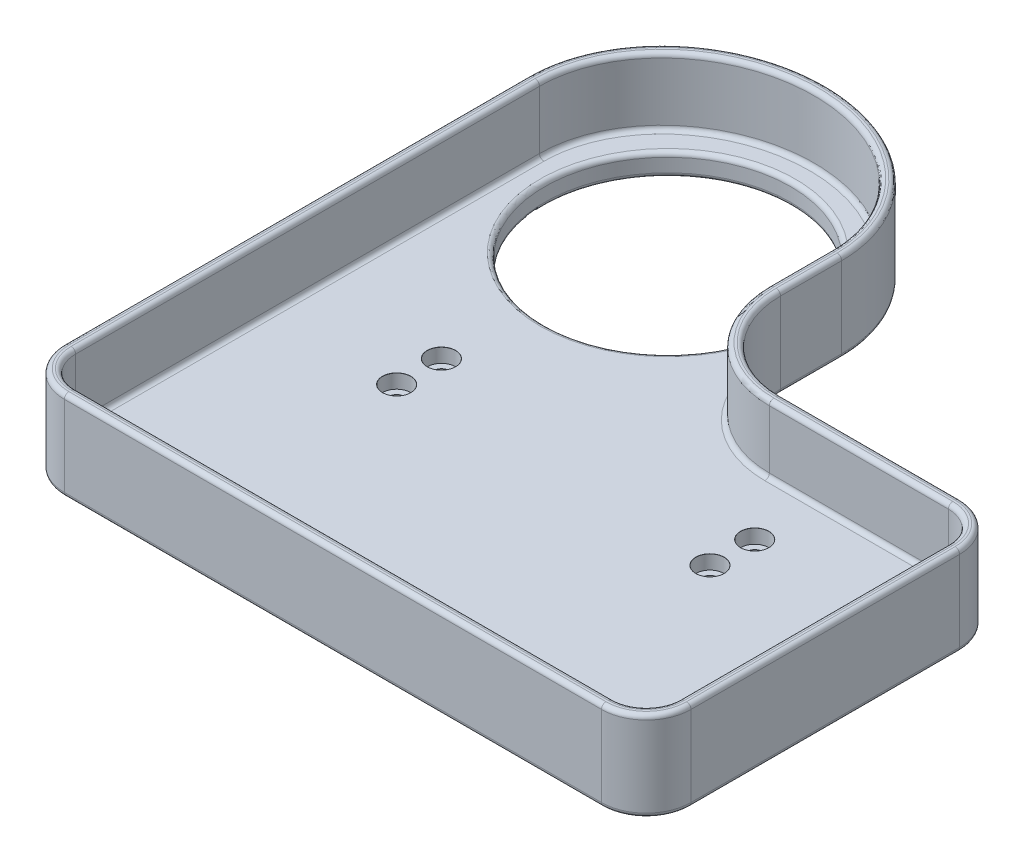
SolidWorks part; units mm, degrees
ref_plane "Front Plane" through (0, 0, 0) normal (0, 0, 1) x (1, 0, 0)
ref_plane "Top Plane" through (0, 0, 0) normal (0, 1, 0) x (1, 0, 0)
ref_plane "Right Plane" through (0, 0, 0) normal (1, 0, 0) x (0, 0, -1)
sketch "Sketch1" plane through (0, 0, 0) normal (0, 1, 0) x (1, 0, 0)
  line L2 (-82.8429, 0) -> (-82.8429, -88.9)
  line L3 (-70.1429, -101.6) -> (82.2571, -101.6)
  line L4 (94.9571, -12.7) -> (94.9571, -88.9)
  line L6 (-82.8429, 42.7307) -> (-82.8429, 0)
  line L9 (31.5939, 0) -> (82.2571, 0)
  line L10 (6.0571, 42.7307) -> (6.0571, 25.4)
  line L11 (31.4571, 0) -> (31.5939, 0)
  line L14 (291.406, 28.105) -> (291.406, -22.695) construction
  line L15 (297.756, 28.105) -> (297.756, -22.695)
  line L16 (285.056, 28.105) -> (285.056, -22.695)
  circle A8 centre (-38.3929, 37.8404) radius 34.925
  arc A9 (297.756, 28.105) -> (285.056, 28.105) centre (291.406, 28.105) ccw
  arc A10 (285.056, -22.695) -> (297.756, -22.695) centre (291.406, -22.695) ccw
  arc A12 (6.0571, 25.4) -> (31.4571, 0) centre (31.4571, 25.4) ccw
  arc A13 (82.2571, -101.6) -> (94.9571, -88.9) centre (82.2571, -88.9) ccw
  arc A14 (-82.8429, -88.9) -> (-70.1429, -101.6) centre (-70.1429, -88.9) ccw
  arc A15 (82.2571, 0) -> (94.9571, -12.7) centre (82.2571, -12.7) cw
  ellipse E0 centre (-38.3929, 42.7307) end of major axis (-82.8429, 42.7307) minor radius 39.8193 (6.0571, 42.7307) -> (-82.8429, 42.7307) ccw
  point P0 (0, 0)
  point P19 (94.9571, -101.6)
  point P22 (-82.8429, -101.6)
  point P35 (291.406, 2.705)
  dimension "D7" = 12.7
  dimension "D8" = 12.7
  dimension "D17" = 69.85
  dimension "D19" = 12.7
  dimension "D4" = 88.9
  dimension "D5" = 25.4
  dimension "D2" = 177.8
  dimension "D3" = 101.6
  dimension "D6" = 82.55
  dimension "D20" = 50.8
extrude "Boss-Extrude1" add sketch "Sketch1" along normal blind 6.35
sketch "Sketch2" plane through (0, 6.35, 0) normal (0, 1, 0) x (1, 0, 0)
  line L0 (-79.6679, 42.7307) -> (-79.6679, -88.9)
  line L1 (-70.1429, -98.425) -> (82.2571, -98.425)
  line L2 (91.7821, -88.9) -> (91.7821, -12.7)
  line L3 (82.2571, -3.175) -> (31.4571, -3.175)
  line L4 (2.8821, 25.4) -> (2.8821, 42.7307)
  line L5 (6.0571, 25.4) -> (6.0571, 42.7307)
  line L6 (-82.8429, 42.7307) -> (-82.8429, -88.9)
  line L7 (-70.1429, -101.6) -> (82.2571, -101.6)
  line L8 (94.9571, -88.9) -> (94.9571, -12.7)
  line L9 (82.2571, 0) -> (31.4571, 0)
  line L10 (6.0571, 25.4) -> (6.0571, 42.7307)
  line L11 (-82.8429, 42.7307) -> (-82.8429, -88.9)
  line L12 (-70.1429, -101.6) -> (82.2571, -101.6)
  line L13 (94.9571, -88.9) -> (94.9571, -12.7)
  line L14 (82.2571, 0) -> (31.4571, 0)
  arc A0 (-79.6679, -88.9) -> (-70.1429, -98.425) centre (-70.1429, -88.9) ccw
  arc A1 (82.2571, -98.425) -> (91.7821, -88.9) centre (82.2571, -88.9) ccw
  arc A2 (91.7821, -12.7) -> (82.2571, -3.175) centre (82.2571, -12.7) ccw
  arc A3 (2.8821, 25.4) -> (31.4571, -3.175) centre (31.4571, 25.4) ccw
  arc A4 (-82.8429, -88.9) -> (-70.1429, -101.6) centre (-70.1429, -88.9) ccw
  arc A5 (82.2571, -101.6) -> (94.9571, -88.9) centre (82.2571, -88.9) ccw
  arc A6 (94.9571, -12.7) -> (82.2571, 0) centre (82.2571, -12.7) ccw
  arc A7 (6.0571, 25.4) -> (31.4571, 0) centre (31.4571, 25.4) ccw
  arc A8 (-82.8429, -88.9) -> (-70.1429, -101.6) centre (-70.1429, -88.9) ccw
  arc A9 (82.2571, -101.6) -> (94.9571, -88.9) centre (82.2571, -88.9) ccw
  arc A10 (94.9571, -12.7) -> (82.2571, 0) centre (82.2571, -12.7) ccw
  arc A11 (6.0571, 25.4) -> (31.4571, 0) centre (31.4571, 25.4) ccw
  ellipse E1 centre (-38.3929, 42.7307) end of major axis (-82.8429, 42.7307) minor radius 39.8193 (6.0571, 42.7307) -> (-82.8429, 42.7307) ccw
  ellipse E2 centre (-38.3929, 42.7307) end of major axis (-82.8429, 42.7307) minor radius 39.8193 (6.0571, 42.7307) -> (-82.8429, 42.7307) ccw
  spline S0 degree 1 poles (2.8821, 42.7307) (-79.6679, 42.7307) knots 0 0 1 1 construction
  spline S1 degree 3 poles (2.8821, 42.7307) (2.8821, 47.479) (0.7796, 56.9766) (-8.3013, 69.1815) (-22.0571, 77.4313) (-38.3929, 80.3469) (-54.7286, 77.4313) (-68.4844, 69.1815) (-77.5653, 56.9766) (-79.6679, 47.479) (-79.6679, 42.7307) knots 3.141593 3.141593 3.141593 3.141593 3.534292 3.926991 4.31969 4.712389 5.105088 5.497787 5.890486 6.283185 6.283185 6.283185 6.283185
  dimension "D1" = 0
  dimension "D2" = 3.175
extrude "Boss-Extrude2" add sketch "Sketch2" along normal blind 19.05
fillet "Fillet1" radius 1.27 20 edges at (-76.8781, 25.4, 95.6352) (6.0571, 25.4, 98.425) (88.9923, 25.4, 95.6352) (91.7821, 25.4, 50.8) (88.9923, 25.4, 5.9648) (56.8571, 25.4, 3.175) (11.2516, 25.4, -5.1944) (2.8821, 25.4, -34.0654) (-79.6679, 25.4, 23.0846) (56.8571, 25.4, 0) (91.2374, 25.4, 3.7197) (94.9571, 25.4, 50.8) (91.2374, 25.4, 97.8803) (6.0571, 25.4, 101.6) (-79.1231, 25.4, 97.8803) (-82.8429, 25.4, 23.0846) (-38.3929, 25.4, -82.55) (6.0571, 25.4, -34.0654) (13.4966, 25.4, -7.4395)
fillet "Fillet2" radius 1.27 21 edges at (-38.3929, 0, -82.55) (-82.8429, 0, 23.0846) (-79.1231, 0, 97.8803) (6.0571, 0, 101.6) (91.2374, 0, 97.8803) (94.9571, 0, 50.8) (91.2374, 0, 3.7197) (56.8571, 0, 0) (13.4966, 0, -7.4395) (6.0571, 0, -34.0654) (2.8821, 6.35, -34.0654) (11.2516, 6.35, -5.1944) (56.8571, 6.35, 3.175) (88.9923, 6.35, 5.9648) (91.7821, 6.35, 50.8) (88.9923, 6.35, 95.6352) (6.0571, 6.35, 98.425) (-76.8781, 6.35, 95.6352) (-79.6679, 6.35, 23.0846) (-38.3929, 6.35, -2.9154)
fillet "Fillet3" radius 1.27 1 edges at (-38.3929, 0, -2.9154)
sketch "Sketch3" plane through (0, 0, 0) normal (0, -1, 0) x (1, 0, 0)
  line L0 (82.2571, 1.27) -> (-81.5729, 1.27) construction
  line L1 (-81.5729, 88.9) -> (-81.5729, -42.7307) construction
  line L2 (-81.5729, 52.07) -> (93.6871, 52.07) construction
  line L3 (93.6871, 12.7) -> (93.6871, 88.9) construction
  line L4 (0, 1.27) -> (0, 52.07) construction
  circle A0 centre (44.45, 20.32) radius 2
  circle A1 centre (44.45, 33.02) radius 2
  circle A2 centre (-44.45, 33.02) radius 2
  circle A3 centre (-44.45, 20.32) radius 2
  point P9 (44.45, 26.67)
  point P22 (-44.45, 26.67)
  dimension "D4" = 4
  dimension "D6" = 4
  dimension "D1" = 50.8
  dimension "D2" = 25.4
  dimension "D3" = 12.7
  dimension "D5" = 44.45
  dimension "D7" = 6.35
sketch "Sketch6" plane through (0, 6.35, 0) normal (0, 1, 0) x (1, 0, 0)
  circle A1 centre (-44.45, -20.32) radius 2
  circle A2 centre (-44.45, -20.32) radius 2
  circle A3 centre (-44.45, -33.02) radius 2
  circle A4 centre (-44.45, -33.02) radius 2
  circle A5 centre (44.45, -33.02) radius 2
  circle A6 centre (44.45, -33.02) radius 2
  circle A7 centre (44.45, -20.32) radius 2
  circle A8 centre (44.45, -20.32) radius 2
  dimension "D1" = 0
  dimension "D2" = 0
  dimension "D3" = 0
  dimension "D4" = 0
hole_wizard "CBORE for M4 SHCS2" positions "3DSketch2" profile "Sketch7" counterbore size "M4" standard "ANSI Metric" end condition through all
sketch3d "3DSketch2"
  point P0 (-44.45, 6.35, 20.32)
  point P3 (-44.45, 6.35, 33.02)
  point P6 (44.45, 6.35, 20.32)
  point P9 (44.45, 6.35, 33.02)
sketch "Sketch7" plane through (-44.45, 6.35, 20.32) normal (1, 0, 0) x (0, 0, 1)
  line L0 (0, 0) -> (0, 8.144)
  line L1 (0, 8.144) -> (2.15, 8.144)
  line L3 (2.15, 8.144) -> (2.15, 4)
  line L4 (4, 4) -> (2.15, 4)
  line L5 (4, 4) -> (4, 0.025)
  line L6 (4, 0.025) -> (4.025, 0)
  line L7 (4.025, 0) -> (0, 0)
  line L8 (-4, 0.025) -> (-4.025, 0) construction
  line L11 (0, -6.35) -> (0, 107.95) construction
  dimension "Thru Hole Dia." = 4.3
  dimension "Thru Hole Depth" = 8.144
  dimension "C'Bore Dia." = 8
  dimension "C'Bore Depth" = 4
  dimension "Near C'Sink Dia." = 8.05
  dimension "Near C'Sink Angle" = 90
